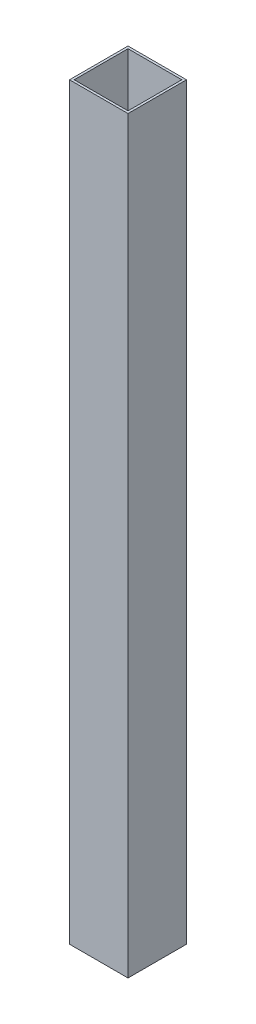
SolidWorks part; units mm, degrees
ref_plane "Front Plane" through (0, 0, 0) normal (0, 0, 1) x (1, 0, 0)
ref_plane "Top Plane" through (0, 0, 0) normal (0, 1, 0) x (1, 0, 0)
ref_plane "Right Plane" through (0, 0, 0) normal (1, 0, 0) x (0, 0, -1)
sketch "Sketch1" plane through (0, 0, 0) normal (0, 1, 0) x (1, 0, 0)
  line L0 (-23, 23) -> (23, 23)
  line L1 (-25, -25) -> (25, -25)
  line L2 (-25, -25) -> (-25, 25)
  line L3 (-25, 25) -> (25, 25)
  line L4 (25, -25) -> (25, 25)
  line L5 (-25, -25) -> (25, 25) construction
  line L6 (-25, 25) -> (25, -25) construction
  line L7 (23, -23) -> (23, 23)
  line L8 (-23, -23) -> (23, -23)
  line L9 (-23, -23) -> (-23, 23)
  point P0 (0, 0)
  dimension "D1" = 50
  dimension "D2" = 2
extrude "Boss-Extrude1" add sketch "Sketch1" along normal blind 640
